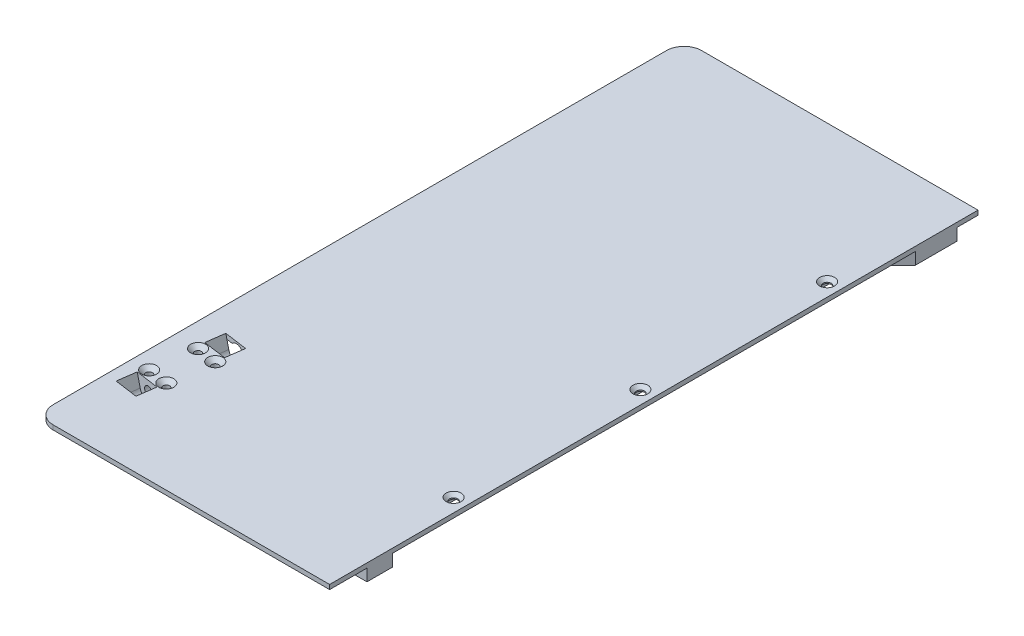
SolidWorks part; units mm, degrees
ref_plane "Front Plane" through (0, 0, 0) normal (0, 0, 1) x (1, 0, 0)
ref_plane "Top Plane" through (0, 0, 0) normal (0, 1, 0) x (1, 0, 0)
ref_plane "Right Plane" through (0, 0, 0) normal (1, 0, 0) x (0, 0, -1)
sketch "Sketch1" plane through (0, 0, 0) normal (0, 1, 0) x (1, 0, 0)
  line L0 (40, 88.1) -> (-40, -88.1) construction
  line L1 (-40, 88.1) -> (40, 88.1) construction
  line L2 (-40, 88.1) -> (-40, -88.1) construction
  line L3 (-40, -88.1) -> (40, -88.1) construction
  line L4 (40, 88.1) -> (40, -88.1) construction
  line L5 (40, 86.8) -> (-34, 86.8)
  line L6 (40, 86.8) -> (40, -86.8)
  line L7 (40, -86.8) -> (-34, -86.8)
  line L8 (-38.7, 82.1) -> (-38.7, -82.1)
  arc A0 (-34, 86.8) -> (-38.7, 82.1) centre (-34, 82.1) ccw
  arc A1 (-34, -86.8) -> (-38.7, -82.1) centre (-34, -82.1) cw
  dimension "D1" = 80
  dimension "D2" = 176.2
  dimension "D3" = 1.3
  dimension "D4" = 1.3
  dimension "D5" = 6
  dimension "D6" = 1.3
extrude "Boss-Extrude1" add sketch "Sketch1" against normal blind 1.2
sketch "Sketch4" plane through (0, -1.2, 0) normal (0, -1, 0) x (-1, 0, 0)
  line L0 (-40, -86.8) -> (-40, 86.8) construction
  line L1 (-40, -76.8) -> (22.7, -76.8)
  line L2 (-40, -76.8) -> (-40, 81.2)
  line L3 (-40, 81.2) -> (22.7, 81.2)
  line L4 (22.7, -76.8) -> (22.7, 81.2)
  line L7 (40, 88.1) -> (40, -88.1) construction
  line L8 (40, 88.1) -> (-40, 88.1) construction
  dimension "D1" = 158
  dimension "D3" = 17.3
  dimension "D2" = 6.9
extrude "Boss-Extrude3" add sketch "Sketch4" along normal blind 3.2
sketch "Sketch6" plane through (0, -1.2, 0) normal (0, -1, 0) x (1, 0, 0)
  line L0 (-40, -88.1) -> (-40, 88.1) construction
  line L1 (-22.8, -76.4) -> (-36.3, -76.4)
  line L2 (-22.8, -76.4) -> (-22.8, -64.75)
  line L3 (-22.8, -64.75) -> (-36.3, -64.75)
  line L4 (-36.3, -76.4) -> (-36.3, -64.75)
  line L5 (-22.8, 70.65) -> (-36.3, 70.65)
  line L6 (-22.8, 70.65) -> (-22.8, 41.45)
  line L7 (-22.8, 41.45) -> (-36.3, 41.45)
  line L8 (-36.3, 70.65) -> (-36.3, 41.45)
  line L9 (-40, -88.1) -> (40, -88.1) construction
  line L10 (-25.5, 56.05) -> (-22.8, 56.05) construction
  line L11 (-22.7, 76.8) -> (-22.7, -81.2) construction
  circle A0 centre (-25.5, -68.35) radius 1.1
  circle A1 centre (-25.5, 56.05) radius 1.1
  dimension "D7" = 2.2
  dimension "D1" = 3.7
  dimension "D2" = 29.2
  dimension "D3" = 17.2
  dimension "D4" = 124.4
  dimension "D5" = 19.75
  dimension "D6" = 2.8
  dimension "D8" = 2.8
  dimension "D9" = 3.6
  dimension "D10" = 5.7
extrude "Boss-Extrude4" add sketch "Sketch6" along normal blind 5.1
sketch "Sketch7" plane through (0, -1.2, 0) normal (0, -1, 0) x (1, 0, 0)
  line L0 (-22.7, 76.8) -> (-22.7, -81.2) construction
  line L1 (-22.8, -76.4) -> (-22.7, -76.4)
  line L2 (-22.8, -76.4) -> (-22.8, -64.75)
  line L3 (-22.8, -64.75) -> (-22.7, -64.75)
  line L4 (-22.7, -76.4) -> (-22.7, -64.75)
  line L5 (-22.8, -64.75) -> (-36.3, -64.75) construction
  line L6 (-22.7, 76.8) -> (-22.7, -81.2) construction
  line L7 (-22.8, 70.65) -> (-22.7, 70.65)
  line L8 (-22.8, 70.65) -> (-22.8, 41.45)
  line L9 (-22.8, 41.45) -> (-22.7, 41.45)
  line L10 (-22.7, 70.65) -> (-22.7, 41.45)
  line L11 (-36.3, 41.45) -> (-22.8, 41.45) construction
extrude "Boss-Extrude5" add sketch "Sketch7" along normal up to surface (3.2 mm away) up to face at (8.65, -4.4, -2.2)
sketch "Sketch9" plane through (0, 0, 0) normal (0, 1, 0) x (1, 0, 0)
  line L0 (-25.9598, -43.3304) -> (-31.3073, -42.5789) construction
  line L1 (-31.3073, -42.5789) -> (-34.9258, -68.3259) construction
  line L2 (-34.9258, -68.3259) -> (-29.5783, -69.0774) construction
  line L3 (-29.5783, -69.0774) -> (-25.9598, -43.3304) construction
  line L4 (-22.8, -70.65) -> (-36.3, -70.65) construction
  line L8 (-36.3, -70.65) -> (-36.3, -41.45) construction
  line L9 (-34.9258, -68.3259) -> (-34.2299, -63.3745)
  line L10 (-34.9258, -68.3259) -> (-29.5783, -69.0774)
  line L11 (-34.2299, -63.3745) -> (-28.8825, -64.1261)
  line L12 (-29.5783, -69.0774) -> (-28.8825, -64.1261)
  line L13 (-25.9598, -43.3304) -> (-31.3073, -42.5789)
  line L14 (-25.9598, -43.3304) -> (-26.6557, -48.2818)
  line L15 (-31.3073, -42.5789) -> (-32.0032, -47.5303)
  line L16 (-26.6557, -48.2818) -> (-32.0032, -47.5303)
  line L17 (-29.5783, -69.0774) -> (-22.6165, -70.0558) construction
  line L18 (-22.6165, -70.0558) -> (-22.7, -70.65) construction
  dimension "D1" = 5.4
  dimension "D3" = 8
  dimension "D2" = 26
  dimension "D4" = 1.3742
  dimension "D5" = 5
  dimension "D6" = 0.6
sketch "Sketch10" plane through (0, -6.3, 0) normal (0, -1, 0) x (1, 0, 0)
  line L0 (-25.9598, 43.3304) -> (-25.6956, 41.45)
  line L1 (-36.3, 41.45) -> (-22.8, 41.45) construction
  line L2 (-25.9598, 43.3304) -> (-39.3399, 41.45)
  line L3 (-36.3, 41.45) -> (-22.7, 41.45) construction
  line L4 (-25.9598, 43.3304) -> (-31.3073, 42.5789) construction
  line L5 (-25.9598, 43.3304) -> (-26.6557, 48.2818) construction
  line L6 (-39.3399, 41.45) -> (-25.6956, 41.45)
  line L7 (-29.5783, 69.0774) -> (-29.7994, 70.65)
  line L8 (-22.7, 70.65) -> (-36.3, 70.65) construction
  line L9 (-29.7994, 70.65) -> (-36.3, 70.65)
  line L10 (-36.3, 70.65) -> (-36.3, 68.1327)
  line L11 (-36.3, 70.65) -> (-36.3, 41.45) construction
  line L12 (-36.3, 68.1327) -> (-29.5783, 69.0774)
  line L13 (-29.5783, 69.0774) -> (-28.8825, 64.1261) construction
  line L14 (-36.3, 70.65) -> (-36.3, 41.45) construction
extrude "Cut-Extrude5" cut sketch "Sketch10" against normal up to surface (5.1 mm away) up to face at (-14.9304, -1.2, -3.7167)
extrude "Cut-Extrude6" cut sketch "Sketch9" against normal blind 5.2
sketch "Sketch11" plane through (-9.3972, 0, 66.8646) normal (-0.1392, 0, 0.9903) x (0.9903, 0, 0.1392)
  line L0 (-19.6768, 0) -> (-25.0768, 0) construction
  line L1 (-22.3768, -2.5) -> (-22.3768, 0) construction
  circle A0 centre (-22.3768, -2.5) radius 1.2
  dimension "D1" = 2.4
  dimension "D2" = 2.5
extrude "Cut-Extrude7" cut sketch "Sketch11" against normal blind 5.4
sketch "Sketch15" plane through (-9.3972, 0, 66.8646) normal (-0.1392, 0, 0.9903) x (0.9903, 0, 0.1392)
  line L0 (-22.3768, -2.5) -> (-24.9722, -3.2442) construction
  line L1 (-19.6768, -5.2) -> (-25.0768, -5.2) construction
  line L2 (-24.9722, -3.2442) -> (-25.9024, 0) construction
  line L3 (-21.5889, 0) -> (-26.8973, 0) construction
  line L4 (-25.9024, 0) -> (-25.0768, 0)
  line L5 (-25.0768, -5.2) -> (-25.0768, 0) construction
  line L6 (-25.0768, 0) -> (-25.0768, -2.8795)
  line L7 (-25.0768, -2.8795) -> (-25.9024, 0)
  circle A0 centre (-22.3768, -2.5) radius 1.2 construction
  dimension "D1" = 16
  dimension "D2" = 2.7
extrude "Cut-Extrude8" cut sketch "Sketch15" along normal up to surface (5 mm away) up to face at (-32.2521, -0.6, 68.7016)
sketch "Sketch17" plane through (-9.3972, 0, 66.8646) normal (-0.1392, 0, 0.9903) x (0.9903, 0, 0.1392)
  line L0 (-25.0768, -2.8795) -> (-24.9722, -3.2442)
  line L1 (-25.9024, 0) -> (-25.0768, -2.8795) construction
  line L2 (-19.6768, -1.2) -> (-19.6768, -6.3) construction
  line L3 (-19.6768, -2.5) -> (-19.6768, -6.3)
  line L4 (-19.6768, -6.3) -> (-25.0768, -6.3)
  line L5 (-25.0768, -6.3) -> (-25.0768, -2.8795)
  line L6 (-26.4645, -6.3) -> (-19.6768, -6.3) construction
  arc A0 (-19.6768, -2.5) -> (-24.9722, -3.2442) centre (-22.3768, -2.5) cw
extrude "Boss-Extrude6" add sketch "Sketch17" along normal up to surface (5 mm away) up to face at (-33.8587, -4.0399, 68.4758)
sketch "Sketch18" plane through (-7.1704, 0, 51.0203) normal (0.1392, 0, -0.9903) x (-0.9903, 0, -0.1392)
  line L3 (25.9024, 0) -> (25.0768, 0)
  line L4 (25.0768, 0) -> (25.0768, -2.8795)
  line L5 (25.0768, -2.8795) -> (25.9024, 0)
  line L6 (25.9024, 0) -> (25.0768, 0)
  line L7 (25.0768, 0) -> (25.0768, -2.8795)
  line L8 (25.0768, -2.8795) -> (25.9024, 0)
  dimension "D1" = 0
extrude "Cut-Extrude9" cut sketch "Sketch18" along normal up to surface (5 mm away) up to face at (-28.6336, -0.6, 42.9547)
sketch "Sketch19" plane through (-7.1704, 0, 51.0203) normal (0.1392, 0, -0.9903) x (-0.9903, 0, -0.1392)
  line L4 (25.0768, -2.8795) -> (24.9722, -3.2442)
  line L5 (19.6768, -2.5) -> (19.6768, -6.3)
  line L6 (19.6768, -6.3) -> (25.0768, -6.3)
  line L7 (25.0768, -6.3) -> (25.0768, -2.8795)
  line L8 (25.0768, -2.8795) -> (24.9722, -3.2442)
  line L9 (19.6768, -2.5) -> (19.6768, -6.3)
  line L10 (19.6768, -6.3) -> (25.0768, -6.3)
  line L11 (25.0768, -6.3) -> (25.0768, -2.8795)
  arc A1 (19.6768, -2.5) -> (24.9722, -3.2442) centre (22.3768, -2.5) ccw
  arc A2 (19.6768, -2.5) -> (24.9722, -3.2442) centre (22.3768, -2.5) ccw
  dimension "D1" = 0
extrude "Boss-Extrude7" add sketch "Sketch19" along normal up to surface (5 mm away) up to face at (-31.2741, -4.0399, 42.5836)
sketch "Sketch20" plane through (0, -6.3, 0) normal (0, -1, 0) x (1, 0, 0)
  line L0 (-36.3, 68.1327) -> (-36.3, 41.8772) construction
  line L1 (-36.3, 59.65) -> (-28.3, 59.65)
  line L2 (-36.3, 59.65) -> (-36.3, 52.45)
  line L3 (-36.3, 52.45) -> (-28.3, 52.45)
  line L4 (-28.3, 59.65) -> (-28.3, 52.45)
  line L5 (-25.5, 56.05) -> (-28.3, 56.05) construction
  dimension "D1" = 7.2
  dimension "D2" = 2.8
extrude "Cut-Extrude10" cut sketch "Sketch20" against normal blind 3.6
sketch "Sketch22" plane through (0, -2.7, 0) normal (0, -1, 0) x (-1, 0, 0)
  line L0 (28.3, -59.65) -> (36.3, -59.65) construction
  line L1 (24.0566, -58.55) -> (26.9434, -58.55)
  line L2 (26.9434, -58.55) -> (28.3868, -56.05) construction
  line L3 (28.3868, -56.05) -> (26.9434, -53.55) construction
  line L4 (26.9434, -53.55) -> (24.0566, -53.55)
  line L5 (24.0566, -53.55) -> (22.6132, -56.05)
  line L6 (22.6132, -56.05) -> (24.0566, -58.55)
  line L7 (26.9434, -58.55) -> (28.3, -58.55)
  line L8 (28.3, -52.45) -> (28.3, -59.65) construction
  line L9 (28.3, -58.55) -> (28.3, -53.55)
  line L10 (28.3, -53.55) -> (26.9434, -53.55)
  circle A0 centre (25.5, -56.05) radius 2.5 construction
  dimension "D1" = 5
extrude "Cut-Extrude12" cut sketch "Sketch22" along normal blind 1.8
ref_plane "Plane1" through (-7.1426, 0, 50.8222) normal (0.1392, 0, -0.9903) x (-0.9903, 0, -0.1392)
sketch "Sketch23" plane through (-7.1704, 0, 51.0203) normal (0.1392, 0, -0.9903) x (-0.9903, 0, -0.1392)
  circle A0 centre (22.3768, -2.5) radius 1.2
  dimension "D1" = 2.4
extrude "Cut-Extrude13" cut sketch "Sketch23" against normal blind 5.4
sketch "Sketch24" plane through (0, 0, 0) normal (0, 1, 0) x (1, 0, 0)
  line L0 (-32.3093, -49.7088) -> (-26.9619, -50.4604) construction
  line L1 (-32.3093, -49.7088) -> (-33.9237, -61.196) construction
  line L2 (-26.9619, -50.4604) -> (-28.5763, -61.9475) construction
  line L3 (-33.9237, -61.196) -> (-28.5763, -61.9475) construction
  line L5 (-32.1249, -42.464) -> (-32.8208, -47.4153) construction
  line L6 (-29.3294, -47.906) -> (-29.6356, -50.0846) construction
  line L7 (-32.8208, -47.4153) -> (-26.6557, -48.2818) construction
  line L8 (-28.8825, -64.1261) -> (-35.0476, -63.2596) construction
  line L9 (-28.1411, -48.073) -> (-30.5178, -47.739) construction
  circle A0 centre (-32.3093, -49.7088) radius 2 construction
  circle A1 centre (-26.9619, -50.4604) radius 2 construction
  circle A2 centre (-28.5763, -61.9475) radius 2 construction
  circle A3 centre (-33.9237, -61.196) radius 2 construction
  circle A4 centre (-32.3093, -49.7088) radius 0.9
  circle A5 centre (-26.9619, -50.4604) radius 0.9
  circle A6 centre (-28.5763, -61.9475) radius 0.9
  circle A7 centre (-33.9237, -61.196) radius 0.9
  point P24 (0, 0)
  dimension "D1" = 4
  dimension "D2" = 1.8
  dimension "D3" = 5.4
  dimension "D4" = 2.2
  dimension "D5" = 2.2
extrude "Cut-Extrude14" cut sketch "Sketch24" against normal through all
chamfer "Chamfer1" distance 1.1 angle 45 4 edges at (-33.9237, 0, 62.096) (-28.5763, 0, 62.8475) (-32.3093, 0, 50.6088) (-26.9619, 0, 51.3604)
sketch "Sketch26" plane through (-6.4746, 0, 46.0689) normal (0.1392, 0, -0.9903) x (-0.9903, 0, -0.1392)
  circle A0 centre (22.3768, -2.5) radius 2
  circle A1 centre (22.3768, -2.5) radius 1.2 construction
  dimension "D1" = 4
extrude "Cut-Extrude15" cut sketch "Sketch26" along normal blind 12
sketch "Sketch27" plane through (-10.0931, 0, 71.8159) normal (-0.1392, 0, 0.9903) x (0.9903, 0, 0.1392)
  circle A0 centre (-22.3768, -2.5) radius 2
  dimension "D1" = 4
extrude "Cut-Extrude16" cut sketch "Sketch27" along normal blind 12
sketch "Sketch28" plane through (0, -6.3, 0) normal (0, -1, 0) x (1, 0, 0)
  line L1 (-28.3868, -68.35) -> (-26.9434, -70.85) construction
  line L2 (-26.9434, -70.85) -> (-24.0566, -70.85)
  line L3 (-24.0566, -70.85) -> (-22.6132, -68.35)
  line L4 (-22.6132, -68.35) -> (-24.0566, -65.85)
  line L5 (-24.0566, -65.85) -> (-26.9434, -65.85)
  line L6 (-26.9434, -65.85) -> (-28.3868, -68.35) construction
  line L8 (-22.8, -64.75) -> (-36.3, -64.75) construction
  line L10 (-26.9434, -70.85) -> (-35.1868, -70.85)
  line L11 (-35.1868, -70.85) -> (-35.1868, -64.75)
  line L12 (-35.1868, -64.75) -> (-28.3868, -64.75)
  line L14 (-28.3868, -64.75) -> (-28.3868, -65.85)
  line L15 (-28.3868, -65.85) -> (-26.9434, -65.85)
  circle A0 centre (-25.5, -68.35) radius 2.5 construction
  circle A1 centre (-25.5, -68.35) radius 1.1 construction
  point P12 (-28.3868, -64.75)
  point P18 (-36.3, -64.75)
  point P19 (-36.3, -70.85)
  dimension "D1" = 5
  dimension "D2" = 6.8
extrude "Cut-Extrude17" cut sketch "Sketch28" along normal blind 1.8 from surface at -3.6 starting at face at (-29.4232, -2.7, 55.9978)
sketch "Sketch29" plane through (0, -6.3, 0) normal (0, -1, 0) x (1, 0, 0)
  line L0 (-22.8, -64.75) -> (-36.3, -64.75) construction
  line L1 (-35.1868, -70.85) -> (-28.3868, -70.85)
  line L2 (-35.1868, -70.85) -> (-35.1868, -64.75)
  line L3 (-35.1868, -64.75) -> (-28.3868, -64.75)
  line L4 (-28.3868, -70.85) -> (-28.3868, -64.75)
  point P6 (0, 0)
  point P7 (-33.1667, -71.726)
  point P8 (0, 0)
  point P11 (0, 0)
extrude "Cut-Extrude18" cut sketch "Sketch29" against normal up to next
sketch "Sketch31" plane through (0, -4.4, 0) normal (0, -1, 0) x (1, 0, 0)
  line L0 (40, 70) -> (32.8, 62.8)
  line L1 (40, -81.2) -> (40, 76.8) construction
  line L2 (32.8, 62.8) -> (32.8, -62.8)
  line L3 (32.8, -62.8) -> (40, -70)
  line L4 (40, -70) -> (40, 70)
  line L5 (40, -88.1) -> (40, 88.1) construction
  point P8 (40, 0)
  dimension "D1" = 140
  dimension "D2" = 45
  dimension "D3" = 45
  dimension "D4" = 7.2
extrude "Cut-Extrude19" cut sketch "Sketch31" against normal up to surface (3.2 mm away) up to face at (-25.5, -1.2, 54.95)
sketch "Sketch32" plane through (0, 0, 0) normal (0, 1, 0) x (1, 0, 0)
  line L0 (36.4, 50) -> (36.4, 0) construction
  line L1 (36.4, 0) -> (36.4, -50) construction
  line L2 (40, 86.8) -> (40, -86.8) construction
  line L3 (36.4, 0) -> (40, 0) construction
  line L5 (40, -70) -> (40, 70) construction
  circle A0 centre (36.4, 50) radius 1.1
  circle A1 centre (36.4, 0) radius 1.1
  circle A2 centre (36.4, -50) radius 1.1
  point P8 (0, 0)
  point P11 (0, 0)
  point P12 (35.5346, 4.861)
  dimension "D1" = 2.2
  dimension "D2" = 50
  dimension "D3" = 3.6
extrude "Cut-Extrude20" cut sketch "Sketch32" against normal up to next
chamfer "Chamfer2" distance 0.9 angle 45 3 edges at (36.4, 0, 51.1) (36.4, 0, 1.1) (36.4, 0, -48.9)
sketch "Sketch33" plane through (0, 0, 0) normal (0, 1, 0) x (1, 0, 0)
  line L0 (-28.6614, -43.1527) -> (-10.8019, -45.6627) construction
  line L1 (-28.6614, -43.1527) -> (-29.3016, -47.708) construction
  line L2 (-29.3016, -47.708) -> (-26.8259, -48.0559) construction
  line L3 (-22.5704, -53.7031) -> (-23.4612, -60.0408) construction
  line L4 (-29.1084, -64.2963) -> (-31.584, -63.9484) construction
  line L5 (-31.584, -63.9484) -> (-32.2242, -68.5036) construction
  line L6 (-32.2242, -68.5036) -> (-14.3647, -71.0136) construction
  line L7 (-25.9598, -43.3304) -> (-26.6557, -48.2818) construction
  line L8 (-28.1411, -48.073) -> (-30.5178, -47.739) construction
  line L9 (-32.8208, -47.4153) -> (-26.6557, -48.2818) construction
  line L10 (28.8162, -74.5036) -> (2.6914, -80.7659) construction
  line L11 (2.6914, -80.7659) -> (9.7561, -89.6538) construction
  line L14 (28.8162, -74.5036) -> (9.7561, -89.6538) construction
  arc A0 (-26.8259, -48.0559) -> (-22.5704, -53.7031) centre (-27.5218, -53.0072) cw construction
  arc A1 (-23.4612, -60.0408) -> (-29.1084, -64.2963) centre (-28.4125, -59.345) cw construction
  arc A2 (-14.3647, -71.0136) -> (2.6914, -80.7659) centre (-18.0527, -97.2547) cw construction
  arc A3 (-10.8019, -45.6627) -> (28.8162, -74.5036) centre (-18.0527, -97.2547) cw construction
  point P17 (-29.3294, -47.906)
  dimension "D2" = 2.5
  dimension "D3" = 5
  dimension "D7" = 26.499
  dimension "D1" = 4.6
  dimension "D4" = 16.4
  dimension "D5" = 0.2
  dimension "D6" = 18.035
  dimension "D8" = 65
  dimension "D9" = 21.48
equation "\"LCD_Height\"= 158mm"
equation "\"LCD_Width\"= 268mm"
equation "\"LCD_PCB_Height\"= 10mm"
equation "\"LCD_PCB_Width\"= 189"
equation "\"LCD_PCB_LOff\"= 38.5"
equation "\"LCD_Thick\"= 2.9mm"
equation "\"LCD_TBezel\"= 4.6mm"
equation "\"LCD_LBezel\"= 4.94mm"
equation "\"LCD_RBezel\"= 6.94mm"
equation "\"LCD_BBezel\"= 9.4mm"
equation "\"Wing_Height\"= 11.5mm"
equation "\"Wing_Width\"= 5mm"
equation "\"Wing_Corner\"= 1mm"
equation "\"Wing_Hole_VOff\"= 3.5mm"
equation "\"Wing_Hole_HOff\"= 2.8mm"
equation "\"Wing_Spacing\"= 128.9 + 2 * \"Wing_Hole_VOff\" - \"Wing_Height\""
equation "\"Wing_TOff\"= 8.35 - \"Wing_Hole_VOff\""
equation "\"Wing_DOff\"= 0.7mm"
equation "\"Wing_Thick\"= 0.3mm"
equation "\"Print_Gap\"= 0.2mm"
equation "\"Pin1_Pos\"= 89.75mm"
equation "\"Pin_Space\"= 0.5mm"
equation "\"Pin_num\"= 30"
equation "\"Min_Thick\"= 1.2mm"
equation "\"Nut_Width\"= 4.8mm"
equation "\"Nut_Height\"= 5.6mm"
equation "\"Nut_Thick\"= 1.6mm"
equation "\"Screw_Hole\"= 2.2mm"
equation "\"Screw_Chamf\"= 0.9mm"
equation "\"Bezel_Gap\"= 0.4mm"
equation "\"USB_Width\"= 16mm"
equation "\"Corner_Radius\"= 6mm"
equation "\"D2@Sketch1\"=\"LCD_Height\" + \"LCD_PCB_Height\" + \"Print_Gap\" + 2 * \"Min_Thick\" + \"Nut_Height\""
equation "\"D3@Sketch1\"=\"Print_Gap\" / 2 + \"Min_Thick\""
equation "\"D4@Sketch1\"=\"Min_Thick\" + \"Print_Gap\" / 2"
equation "\"D5@Sketch1\"=\"Corner_Radius\""
equation "\"D1@Boss-Extrude1\"=\"Min_Thick\""
equation "\"D6@Sketch1\"=\"Print_Gap\" / 2 + \"Min_Thick\""
equation "\"D1@Sketch4\"=\"LCD_Height\""
equation "\"D1@Boss-Extrude3\"=8 - \"Min_Thick\" - 0.6 - \"Print_Gap\" / 2 - \"LCD_Thick\""
equation "\"D3@Sketch4\"=\"Min_Thick\" + \"Print_Gap\" / 2 + \"USB_Width\""
equation "\"D1@Sketch6\"=3 * \"Min_Thick\" + \"Print_Gap\" / 2"
equation "\"D2@Sketch6\"=\"Nut_Width\" + 2 * \"Min_Thick\" + 22"
equation "\"D3@Sketch6\"= \"Min_Thick\" + \"USB_Width\""
equation "\"D4@Sketch6\"=\"Wing_Spacing\""
equation "\"D5@Sketch6\"=\"Min_Thick\" + \"Nut_Height\" + \"Print_Gap\"/2 + \"Wing_TOff\" + \"Wing_Height\" - \"Wing_Hole_VOff\""
equation "\"D6@Sketch6\"=\"Wing_Hole_HOff\""
equation "\"D7@Sketch6\"=\"Screw_Hole\""
equation "\"D8@Sketch6\"=\"Wing_Hole_HOff\""
equation "\"D9@Sketch6\"=\"Nut_Width\" / 2 + \"Min_Thick\""
equation "\"D10@Sketch6\"= \"Screw_Chamf\" + \"Screw_Hole\" / 2 + \"Min_Thick\" + \"Nut_Width\" / 2 + \"Print_Gap\" / 2"
equation "\"D1@Boss-Extrude4\"= 8 - 0.6 - \"Min_Thick\" - \"Wing_DOff\" - \"Print_Gap\"/2 - \"Wing_Thick\""
equation "\"D2@Sketch4\"=\"Min_Thick\" + \"Nut_Height\" + \"Print_Gap\" / 2"
equation "\"Stand_Tilt\"= 8"
equation "\"Screen_Tilt\"= 24"
equation "\"Stand_Splay\"= 16"
equation "\"D1@Sketch9\"=2 * 1.6 + 1.8 + 2 * \"Print_Gap\" "
equation "\"D3@Sketch9\"=\"Stand_Tilt\""
equation "\"D4@Sketch9\"=2.7 * tan(\"Stand_Splay\") + \"Min_Thick\" / 2"
equation "\"D6@Sketch9\"=\"Min_Thick\" / 2"
equation "\"D1@Sketch11\"=\"Screw_Hole\" + \"Print_Gap\""
equation "\"D1@Sketch15\"=\"Stand_Splay\""
equation "\"D1@Sketch20\"=\"Nut_Width\"  + \"Min_Thick\" * 2"
equation "\"D2@Sketch20\"= 0.5 * \"Nut_Height\""
equation "\"D1@Cut-Extrude10\"=\"Nut_Thick\" + \"Print_Gap\" + \"Min_Thick\" * 1.5"
equation "\"D1@Sketch22\"=\"Nut_Width\" + \"Print_Gap\""
equation "\"D1@Cut-Extrude12\" = \"Nut_Thick\" + \"Print_Gap\""
equation "\"D3@Sketch24\"= 1.8 + 2.4 + \"Min_Thick\""
equation "\"D4@Sketch24\"=2 + .2"
equation "\"D5@Sketch24\"=2 + .2"
equation "\"D1@Chamfer1\"= \"Print_Gap\" + \"Screw_Chamf\""
equation "\"D1@Sketch28\"=\"Nut_Width\" + \"Print_Gap\""
equation "\"D2@Sketch28\"=\"Nut_Height\" + \"Min_Thick\""
equation "\"D1@Cut-Extrude17\"=\"Nut_Thick\" + \"Print_Gap\""
equation "\"D4@Sketch31\"=\"Nut_Width\" + 2 * \"Min_Thick\""
equation "\"D1@Sketch32\"=\"Screw_Hole\""
equation "\"D3@Sketch32\"=\"Nut_Width\" / 2 + \"Min_Thick\""
equation "\"D1@Chamfer2\"=\"Screw_Chamf\""
equation "\"D4@Sketch33\"=16 + 2 * \"Print_Gap\""
equation "\"D5@Sketch33\"=\"Print_Gap\""
